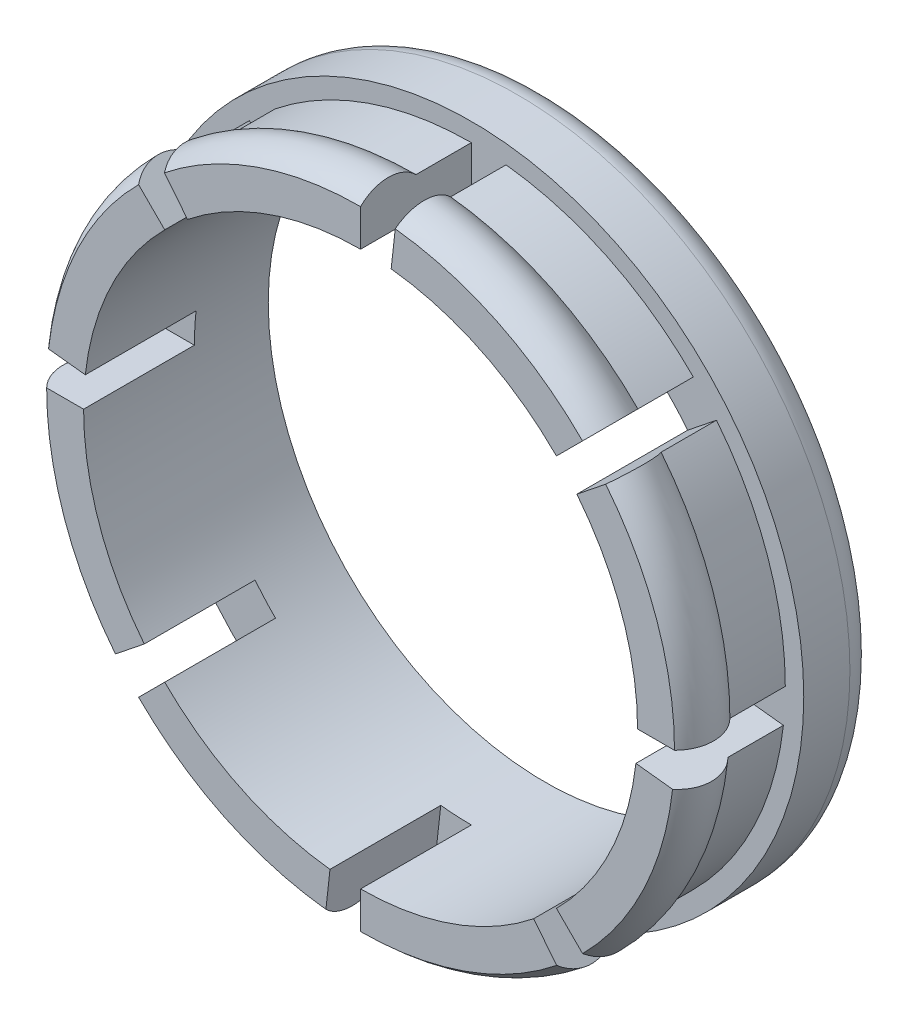
SolidWorks part; units mm, degrees
ref_plane "Front Plane" through (0, 0, 0) normal (0, 0, 1) x (1, 0, 0)
ref_plane "Top Plane" through (0, 0, 0) normal (0, 1, 0) x (1, 0, 0)
ref_plane "Right Plane" through (0, 0, 0) normal (1, 0, 0) x (0, 0, -1)
sketch "Sketch1" plane through (0, 0, 0) normal (0, 0, 1) x (1, 0, 0)
  circle A0 centre (0, 0) radius 9
  circle A2 centre (0, 0) radius 7.5
extrude "Boss-Extrude1" add sketch "Sketch1" along normal blind 5
ref_axis "Axis1" through (0, 0, 5) along (0, 0, -1)
sketch "Sketch2" plane through (0, 0, 0) normal (0, 1, 0) x (1, 0, 0)
  line L0 (-9, -5) -> (-8.5, -5)
  line L1 (-9, -5) -> (9, -5) construction
  line L2 (-8.5, -3.5) -> (-8.5, -2)
  line L3 (-8.5, -2) -> (-9, -2)
  line L4 (-9, 0) -> (-9, -5) construction
  line L5 (-8.25, 0) -> (-9, 0)
  line L6 (-9, 0) -> (-9, -0.75)
  line L7 (-9, -2) -> (-9, -5)
  arc A1 (-8.25, 0) -> (-9, -0.75) centre (-8.25, -0.75) ccw
  arc A2 (-8.5, -5) -> (-8.5, -3.5) centre (-7.75, -4.25) cw
revolve "Cut-Revolve1" cut sketch "Sketch2" angle 360 about axis through (0, 0, 5) along (0, 0, -1)
sketch "Sketch3" plane through (0, 0, 5) normal (0, 0, 1) x (1, 0, 0)
  line L0 (0, -7.5) -> (0, -9)
  line L1 (-5.3033, -5.3033) -> (-6.364, -6.364)
  line L2 (-7.5, 0) -> (-9, 0)
  line L3 (-5.3033, 5.3033) -> (-6.364, 6.364)
  line L5 (0, 7.5) -> (0, 9)
  line L10 (5.3033, -5.3033) -> (6.364, -6.364)
  line L12 (5.3033, 5.3033) -> (6.364, 6.364)
  line L14 (7.5, 0) -> (9, 0)
  line L16 (-0.8282, -7.4541) -> (-0.9939, -8.945)
  line L17 (-5.8565, -4.6852) -> (-7.0278, -5.6223)
  line L18 (-7.4541, 0.8282) -> (-8.945, 0.9939)
  line L19 (-4.6852, 5.8565) -> (-5.6223, 7.0278)
  line L20 (0.8282, 7.4541) -> (0.9939, 8.945)
  line L21 (5.8565, 4.6852) -> (7.0278, 5.6223)
  line L22 (7.4541, -0.8282) -> (8.945, -0.9939)
  line L23 (4.6852, -5.8565) -> (5.6223, -7.0278)
  arc A1 (-0.8282, -7.4541) -> (0, -7.5) centre (0, 0) ccw
  arc A2 (-0.9939, -8.945) -> (0, -9) centre (0, 0) ccw
  arc A3 (-7.0278, -5.6223) -> (-6.364, -6.364) centre (0, 0) ccw
  arc A4 (-5.8565, -4.6852) -> (-5.3033, -5.3033) centre (0, 0) ccw
  arc A5 (-7.4541, 0.8282) -> (-7.5, 0) centre (0, 0) ccw
  arc A6 (-8.945, 0.9939) -> (-9, 0) centre (0, 0) ccw
  arc A7 (-5.6223, 7.0278) -> (-6.364, 6.364) centre (0, 0) ccw
  arc A8 (-4.6852, 5.8565) -> (-5.3033, 5.3033) centre (0, 0) ccw
  arc A9 (0.8282, 7.4541) -> (0, 7.5) centre (0, 0) ccw
  arc A10 (0.9939, 8.945) -> (0, 9) centre (0, 0) ccw
  arc A11 (7.0278, 5.6223) -> (6.364, 6.364) centre (0, 0) ccw
  arc A12 (5.8565, 4.6852) -> (5.3033, 5.3033) centre (0, 0) ccw
  arc A13 (7.4541, -0.8282) -> (7.5, 0) centre (0, 0) ccw
  arc A14 (8.945, -0.9939) -> (9, 0) centre (0, 0) ccw
  arc A15 (5.6223, -7.0278) -> (6.364, -6.364) centre (0, 0) ccw
  arc A16 (4.6852, -5.8565) -> (5.3033, -5.3033) centre (0, 0) ccw
extrude "Cut-Extrude1" cut sketch "Sketch3" against normal up to surface (3 mm away) up to face at (9, 0, 2)
